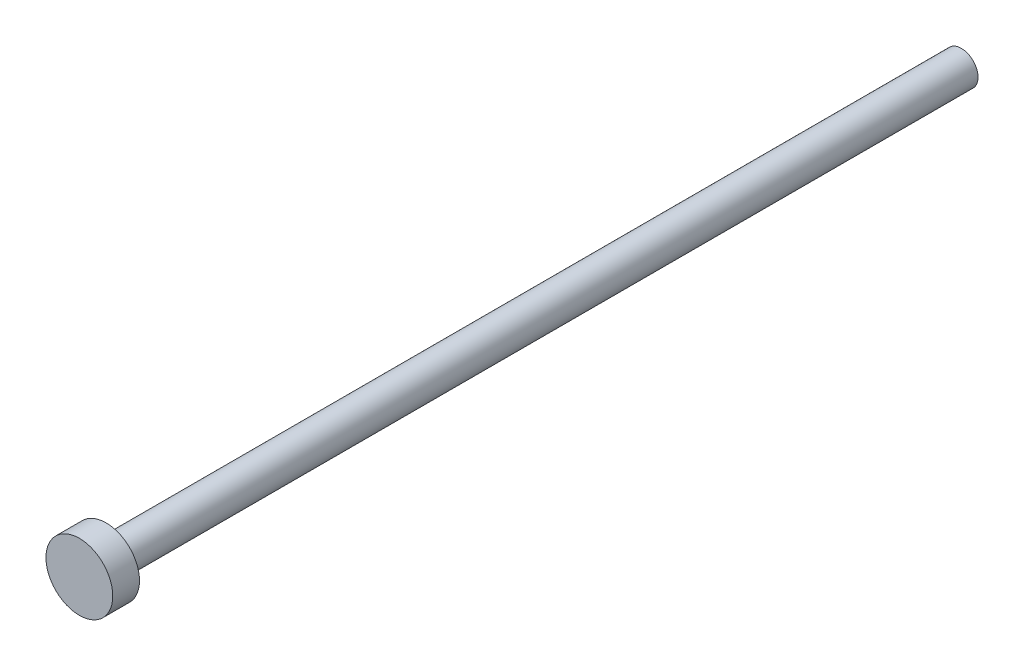
SolidWorks part; units mm, degrees
ref_plane "Front Plane" through (0, 0, 0) normal (0, 0, 1) x (1, 0, 0)
ref_plane "Top Plane" through (0, 0, 0) normal (0, 1, 0) x (1, 0, 0)
ref_plane "Right Plane" through (0, 0, 0) normal (1, 0, 0) x (0, 0, -1)
sketch "Sketch1" plane through (0, 0, 0) normal (0, 0, 1) x (1, 0, 0)
  circle A0 centre (0, 0) radius 1.25
  dimension "D1" = 2.5
extrude "Boss-Extrude1" add sketch "Sketch1" along normal blind 1
sketch "Sketch2" plane through (0, 0, 0) normal (0, 0, -1) x (-1, 0, 0)
  circle A0 centre (0, 0) radius 0.625
  dimension "D1" = 1.25
extrude "Boss-Extrude2" add sketch "Sketch2" along normal blind 32
